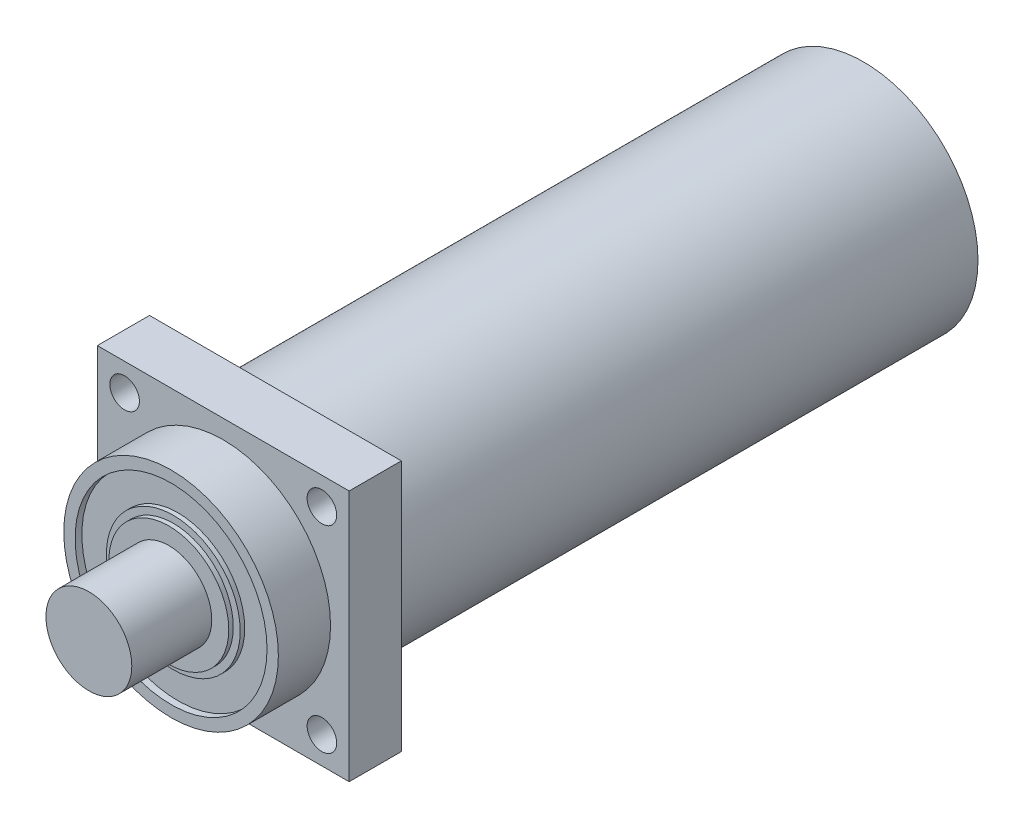
SolidWorks part; units mm, degrees
ref_plane "Front Plane" through (0, 0, 0) normal (0, 0, 1) x (1, 0, 0)
ref_plane "Top Plane" through (0, 0, 0) normal (0, 1, 0) x (1, 0, 0)
ref_plane "Right Plane" through (0, 0, 0) normal (1, 0, 0) x (0, 0, -1)
sketch "Sketch2" plane through (0, 0, 0) normal (0, 0, 1) x (1, 0, 0)
  line L1 (13.97, -13.97) -> (-13.97, -13.97)
  line L2 (13.97, -13.97) -> (13.97, 13.97)
  line L3 (13.97, 13.97) -> (-13.97, 13.97)
  line L4 (-13.97, -13.97) -> (-13.97, 13.97)
  line L5 (13.97, -13.97) -> (-13.97, 13.97) construction
  line L6 (13.97, 13.97) -> (-13.97, -13.97) construction
  point P0 (0, 0)
  dimension "D1" = 27.94
  dimension "D2" = 27.94
extrude "Boss-Extrude1" add sketch "Sketch2" along normal blind 5.79
sketch "Sketch3" plane through (0, 0, 5.79) normal (0, 0, 1) x (1, 0, 0)
  circle A0 centre (0, 0) radius 11.905
  dimension "D1" = 23.81
extrude "Boss-Extrude2" add sketch "Sketch3" along normal blind 5.79
sketch "Sketch4" plane through (0, 0, 11.58) normal (0, 0, 1) x (1, 0, 0)
  circle A0 centre (0, 0) radius 4.765
  dimension "D1" = 9.53
extrude "Boss-Extrude3" add sketch "Sketch4" along normal blind 9.12
sketch "Sketch5" plane through (0, 0, 0) normal (0, 0, -1) x (-1, 0, 0)
  circle A0 centre (0, 0) radius 12.7
  dimension "D1" = 25.4
extrude "Boss-Extrude4" add sketch "Sketch5" along normal blind 65.25
sketch "Sketch6" plane through (0, 0, 11.58) normal (0, 0, 1) x (1, 0, 0)
  circle A0 centre (0, 0) radius 10.6489
  circle A1 centre (0, 0) radius 4.765
extrude "Cut-Extrude1" cut sketch "Sketch6" against normal blind 0.75
sketch "Sketch7" plane through (0, 0, 10.83) normal (0, 0, 1) x (1, 0, 0)
  circle A0 centre (0, 0) radius 7.421
extrude "Boss-Extrude5" add sketch "Sketch7" along normal blind 0.5
sketch "Sketch8" plane through (0, 0, 11.33) normal (0, 0, 1) x (1, 0, 0)
  circle A0 centre (0, 0) radius 6.6513
extrude "Boss-Extrude6" add sketch "Sketch8" along normal blind 0.5
sketch "Sketch9" plane through (0, 0, 5.79) normal (0, 0, 1) x (1, 0, 0)
  line L1 (10.945, -10.945) -> (-10.945, -10.945) construction
  line L2 (10.945, -10.945) -> (10.945, 10.945) construction
  line L3 (10.945, 10.945) -> (-10.945, 10.945) construction
  line L4 (-10.945, -10.945) -> (-10.945, 10.945) construction
  line L5 (10.945, -10.945) -> (-10.945, 10.945) construction
  line L6 (10.945, 10.945) -> (-10.945, -10.945) construction
  circle A0 centre (-10.945, 10.945) radius 1.64
  circle A1 centre (10.945, 10.945) radius 1.64
  circle A2 centre (10.945, -10.945) radius 1.64
  circle A3 centre (-10.945, -10.945) radius 1.64
  point P0 (0, 0)
  dimension "D3" = 3.28
  dimension "D1" = 21.89
  dimension "D2" = 21.89
extrude "Cut-Extrude2" cut sketch "Sketch9" against normal blind 10.5
